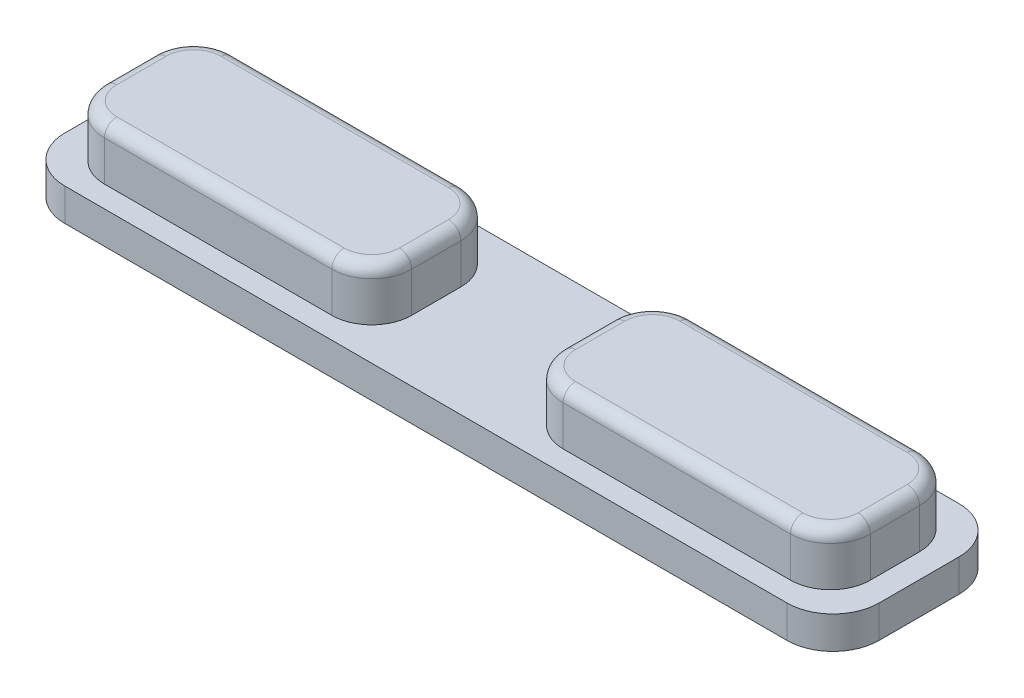
SolidWorks part; units mm, degrees
ref_plane "Front Plane" through (0, 0, 0) normal (0, 0, 1) x (1, 0, 0)
ref_plane "Top Plane" through (0, 0, 0) normal (0, 1, 0) x (1, 0, 0)
ref_plane "Right Plane" through (0, 0, 0) normal (1, 0, 0) x (0, 0, -1)
sketch "Sketch1" plane through (0, 0, 0) normal (0, 1, 0) x (1, 0, 0)
  line L1 (-13.25, -2.8) -> (13.25, -2.8)
  line L2 (-13.25, -2.8) -> (-13.25, 2.8)
  line L3 (-13.25, 2.8) -> (13.25, 2.8)
  line L4 (13.25, -2.8) -> (13.25, 2.8)
  line L5 (-13.25, -2.8) -> (13.25, 2.8) construction
  line L6 (-13.25, 2.8) -> (13.25, -2.8) construction
  point P0 (0, 0)
  dimension "D1" = 5.6
  dimension "26.5" = 26.5
extrude "Boss-Extrude1" add sketch "Sketch1" along normal blind 1.056 contours L1 L4 L3 L2
sketch "Sketch2" plane through (0, 1.056, 0) normal (0, 1, 0) x (1, 0, 0)
  line L0 (0, -1000) -> (0, 49000) construction
  line L1 (-1000, 0) -> (49000, 0) construction
  line L3 (2.465, -2.1) -> (12.465, -2.1)
  line L4 (2.465, -2.1) -> (2.465, 2.1)
  line L5 (2.465, 2.1) -> (12.465, 2.1)
  line L6 (12.465, -2.1) -> (12.465, 2.1)
  line L7 (2.465, -2.1) -> (12.465, 2.1) construction
  line L8 (2.465, 2.1) -> (12.465, -2.1) construction
  point P4 (7.465, 0)
  dimension "D1" = 4.93
  dimension "D2" = 10
  dimension "D3" = 4.2
extrude "Boss-Extrude2" add sketch "Sketch2" along normal blind 1.7
fillet "Fillet1" radius 1.5 4 edges at (13.25, 0.528, -2.8) (13.25, 0.528, 2.8) (-13.25, 0.528, -2.8) (-13.25, 0.528, 2.8)
fillet "Fillet2" radius 1.3 4 edges at (2.465, 1.906, -2.1) (12.465, 1.906, -2.1) (12.465, 1.906, 2.1) (2.465, 1.906, 2.1)
fillet "Fillet3" radius 0.4 8 edges at (12.0842, 2.756, -1.7192) (12.465, 2.756, 0) (12.0842, 2.756, 1.7192) (7.465, 2.756, 2.1) (2.8458, 2.756, 1.7192) (2.465, 2.756, 0) (2.8458, 2.756, -1.7192) (7.465, 2.756, -2.1)
mirror "Mirror2" about plane through (0, 0, 0) normal (1, 0, 0) of "Fillet2", "Fillet3", "Boss-Extrude2"
